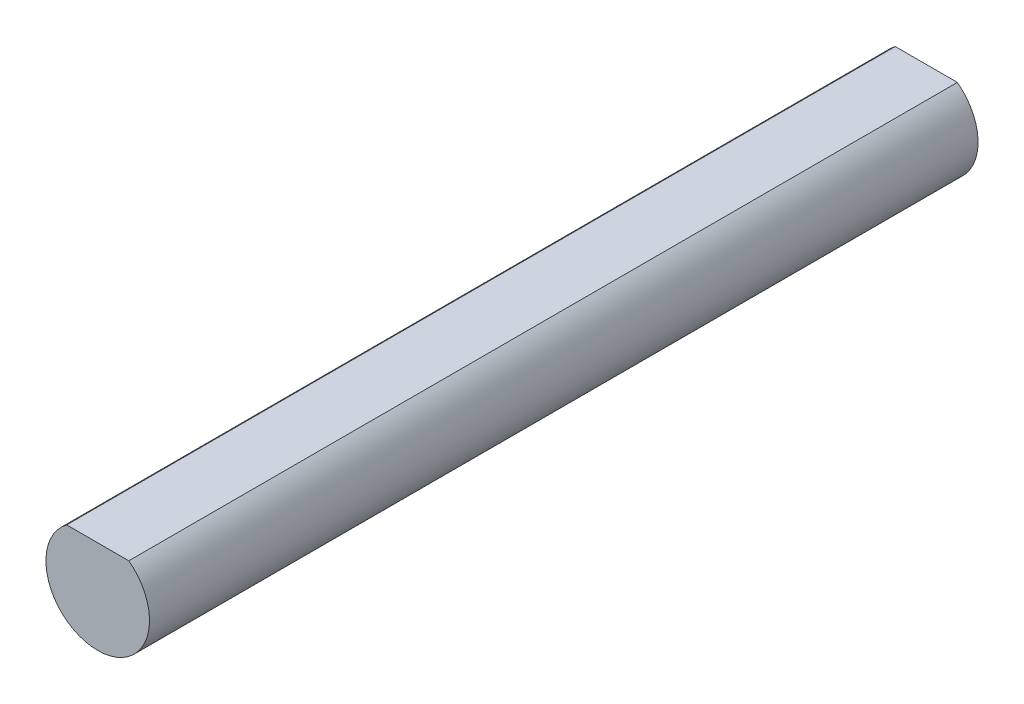
SolidWorks part; units mm, degrees
material "Acier allié inoxydable"
ref_plane "Plan de face" through (0, 0, 0) normal (0, 0, 1) x (1, 0, 0)
ref_plane "Plan de dessus" through (0, 0, 0) normal (0, 1, 0) x (1, 0, 0)
ref_plane "Plan de droite" through (0, 0, 0) normal (1, 0, 0) x (0, 0, -1)
sketch "Esquisse2" plane through (0, 0, 0) normal (0, 0, 1) x (1, 0, 0)
  line L0 (-1.905, 2.54) -> (1.905, 2.54)
  arc A0 (-1.905, 2.54) -> (1.905, 2.54) centre (0, 0) ccw
  point P4 (0, -3.175)
  dimension "D1" = 3.175
  dimension "D2" = 5.715
  dimension "D3" = 2.54
extrude "Boss.-Extru.1" add sketch "Esquisse2" along normal blind 50.8 contours A0 L0
